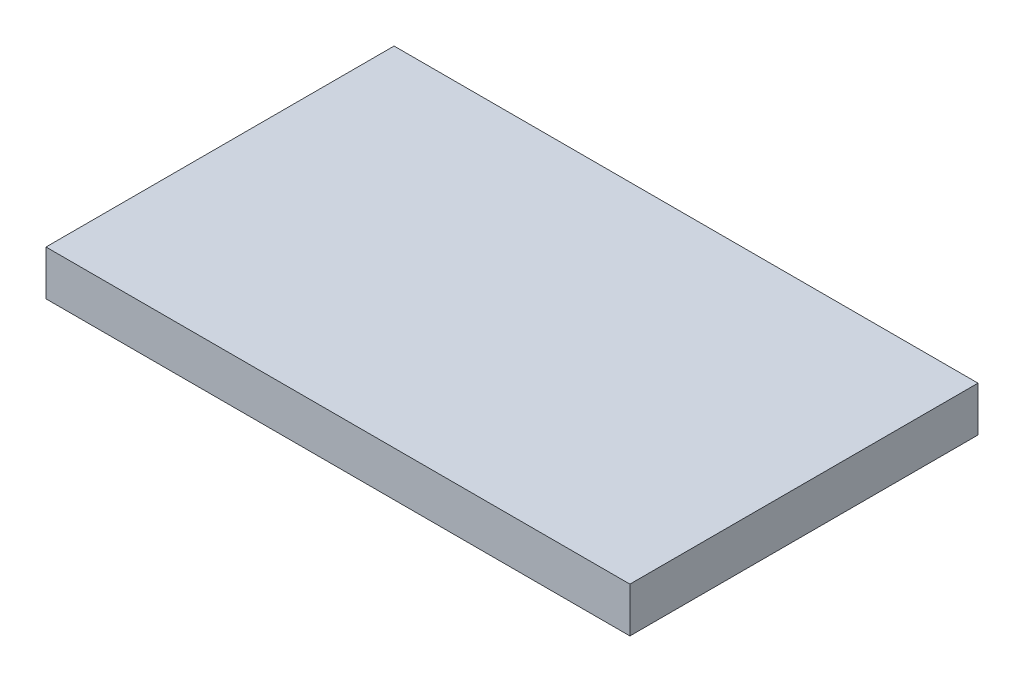
SolidWorks part; units mm, degrees
ref_plane "Front Plane" through (0, 0, 0) normal (0, 0, 1) x (1, 0, 0)
ref_plane "Top Plane" through (0, 0, 0) normal (0, 1, 0) x (1, 0, 0)
ref_plane "Right Plane" through (0, 0, 0) normal (1, 0, 0) x (0, 0, -1)
sketch "Sketch1" plane through (0, 0, 0) normal (0, 1, 0) x (1, 0, 0)
  line L1 (-13, 7.75) -> (13, 7.75)
  line L2 (-13, 7.75) -> (-13, -7.75)
  line L3 (-13, -7.75) -> (13, -7.75)
  line L4 (13, 7.75) -> (13, -7.75)
  line L5 (-13, 7.75) -> (13, -7.75) construction
  line L6 (-13, -7.75) -> (13, 7.75) construction
  point P0 (0, 0)
  dimension "D1" = 26
  dimension "D2" = 15.5
extrude "Boss-Extrude1" add sketch "Sketch1" along normal blind 2
sketch "Sketch3" plane through (0, 2, 0) normal (0, 1, 0) x (1, 0, 0)
  line L0 (-13, 7.75) -> (-13, -7.75) construction
  line L1 (-13, 7.5) -> (13, 7.5)
  line L2 (-13, 7.5) -> (-13, 5)
  line L3 (-13, 5) -> (13, 5)
  line L4 (13, 7.5) -> (13, 5)
  line L5 (13, 7.75) -> (-13, 7.75) construction
  dimension "D1" = 2.5
  dimension "D2" = 26
  dimension "D3" = 0.25
extrude "Boss-Extrude2" [suppressed] add sketch "Sketch3" along normal blind 8
